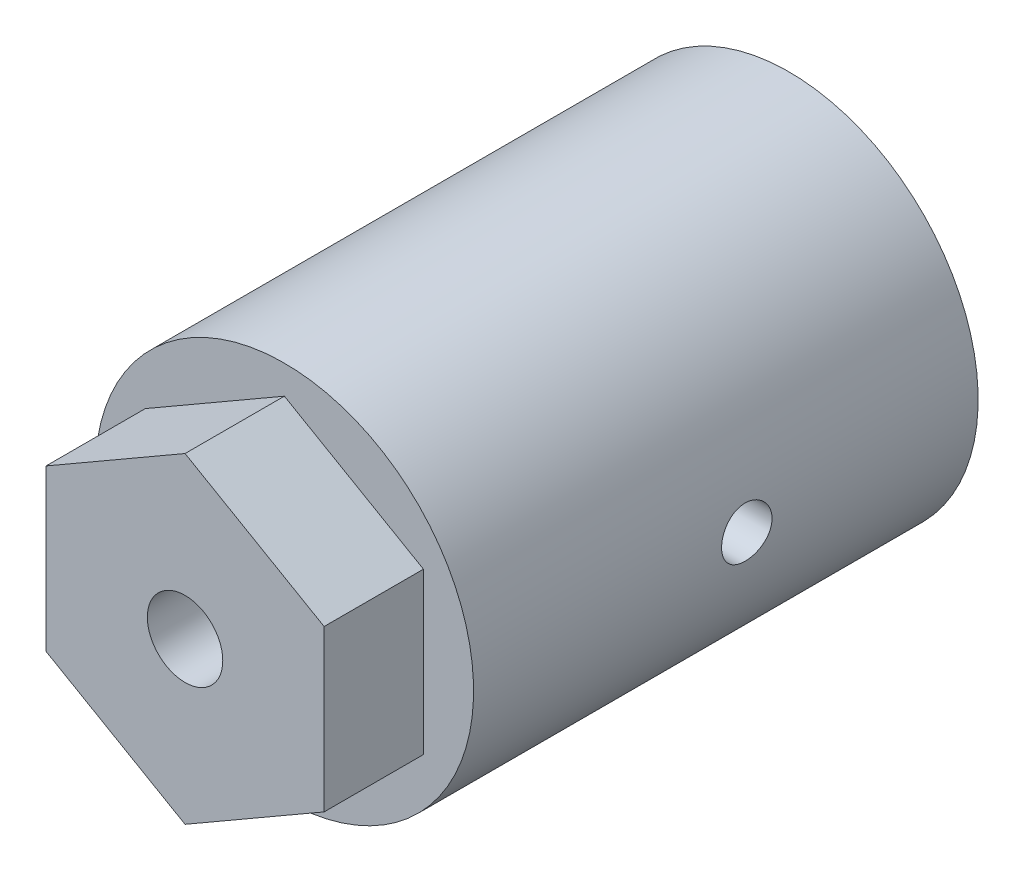
SolidWorks part; units mm, degrees
material "6061-T6 (SS)"
ref_plane "Front Plane" through (0, 0, 0) normal (0, 0, 1) x (1, 0, 0)
ref_plane "Top Plane" through (0, 0, 0) normal (0, 1, 0) x (1, 0, 0)
ref_plane "Right Plane" through (0, 0, 0) normal (1, 0, 0) x (0, 0, -1)
sketch "Sketch1" plane through (0, 0, 0) normal (0, 0, 1) x (1, 0, 0)
  line L1 (0, 8.0829) -> (-7, 4.0415)
  line L2 (-7, 4.0415) -> (-7, -4.0415)
  line L3 (-7, -4.0415) -> (0, -8.0829)
  line L4 (0, -8.0829) -> (7, -4.0415)
  line L5 (7, -4.0415) -> (7, 4.0415)
  line L6 (7, 4.0415) -> (0, 8.0829)
  circle A1 centre (0, 0) radius 7 construction
extrude "Boss-Extrude2" add sketch "Sketch1" along normal blind 5
sketch "Sketch2" plane through (0, 0, 0) normal (0, 0, -1) x (-1, 0, 0)
  circle A0 centre (0, 0) radius 9.525
  dimension "D1" = 19.05
extrude "Boss-Extrude3" add sketch "Sketch2" along normal blind 25.4
sketch "Sketch3" plane through (0, 0, -25.4) normal (0, 0, -1) x (-1, 0, 0)
  circle A0 centre (0, 0) radius 3.9688
  dimension "D1" = 7.9375
extrude "Cut-Extrude1" cut sketch "Sketch3" against normal blind 19.05
sketch "Sketch4" plane through (0, 0, 5) normal (0, 0, 1) x (1, 0, 0)
  circle A0 centre (0, 0) radius 1.27
  dimension "D1" = 2.54
extrude "Cut-Extrude2" cut sketch "Sketch4" against normal blind 19.05
hole_wizard "#10-24 Tapped Hole1" positions "3DSketch1" profile "Sketch5" tap size "#10-24" standard "Ansi Inch"
sketch3d "3DSketch1"
  line L0 (0, 0, -6.35) -> (0, 0, 5) construction
  point P0 (0, 0, 5)
sketch "Sketch5" plane through (0, 0, 5) normal (1, 0, 0) x (0, -1, 0)
  line L0 (0, 0) -> (0, 16.0908)
  line L1 (0, 16.0908) -> (1.8986, 14.95)
  line L2 (1.8986, 14.95) -> (1.8986, 0)
  line L5 (1.8986, 0) -> (0, 0)
  line L10 (0, 16.0908) -> (-1.8987, 14.95) construction
  line L11 (0, -6.35) -> (0, 107.95) construction
  dimension "Tap Drill Dia." = 3.7973
  dimension "Tap Drill Depth" = 14.95
  dimension "Drill Angle" = 118
cosmetic thread "Hole Thread1" parameters "D1"=9.65, "D2"=4.826
ref_plane "Plane1" through (9.525, 0, 0) normal (1, 0, 0) x (0, 0, -1)
sketch "Sketch6" plane through (9.525, 0, 0) normal (1, 0, 0) x (0, 0, -1)
  circle A0 centre (13.7551, 0) radius 1.27
  dimension "D1" = 2.54
extrude "Cut-Extrude3" cut sketch "Sketch6" against normal blind 8
